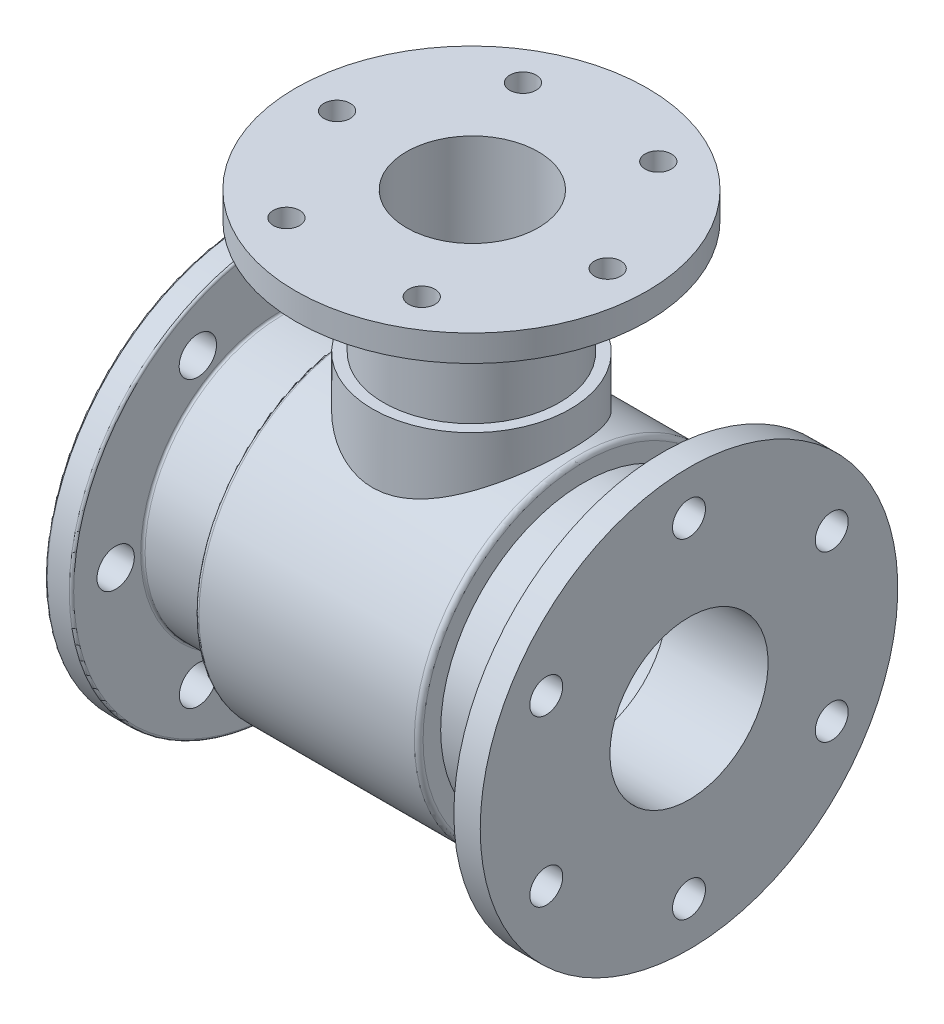
SolidWorks part; units mm, degrees
ref_plane "Front Plane" through (0, 0, 0) normal (0, 0, 1) x (1, 0, 0)
ref_plane "Top Plane" through (0, 0, 0) normal (0, 1, 0) x (1, 0, 0)
ref_plane "Right Plane" through (0, 0, 0) normal (1, 0, 0) x (0, 0, -1)
sketch "Sketch1" plane through (0, 0, 0) normal (0, 0, 1) x (1, 0, 0)
  line L0 (0, 0) -> (0, 122302.881) construction
  line L1 (0, 0) -> (122302.881, 0) construction
  line L2 (-87, -47.5) -> (-87, -52.5)
  line L3 (-87, -52.5) -> (-99, -52.5)
  line L4 (-99, -52.5) -> (-99, -95)
  line L5 (-99, -95) -> (-87, -95)
  line L6 (-87, -95) -> (-87, -62.5)
  line L7 (-87, -62.5) -> (-51, -62.5)
  line L8 (-51, -62.5) -> (-51, -73)
  line L9 (-49, -75) -> (49, -75)
  line L10 (51, -73) -> (51, -65)
  line L11 (51, -65) -> (73, -65)
  line L12 (73, -65) -> (73, -50)
  line L13 (73, -50) -> (87, -50)
  line L14 (87, -50) -> (87, -95)
  line L15 (87, -95) -> (99, -95)
  line L16 (99, -95) -> (99, -36)
  line L17 (99, -36) -> (53, -36)
  line L18 (53, -36) -> (53, -41.5)
  line L19 (51, -43.5) -> (36, -43.5)
  line L20 (36, -43.5) -> (36, -50.5)
  line L21 (34, -52.5) -> (-34, -52.5)
  line L22 (-36, -50.5) -> (-36, -47.5)
  line L23 (-36, -47.5) -> (-87, -47.5)
  line L24 (53, -41.5) -> (51, -43.5)
  arc A0 (-51, -73) -> (-49, -75) centre (-49, -73) ccw
  arc A1 (49, -75) -> (51, -73) centre (49, -73) ccw
  arc A2 (36, -50.5) -> (34, -52.5) centre (34, -50.5) cw
  arc A3 (-34, -52.5) -> (-36, -50.5) centre (-34, -50.5) cw
  point P23 (53, -43.5)
  point P28 (80, -50)
  point P29 (62, -65)
  dimension "D16" = 2
  dimension "D1" = 26
  dimension "D2" = 2
  dimension "D3" = 63
  dimension "D4" = 135
  dimension "D5" = 150
  dimension "D6" = 12
  dimension "D7" = 72
  dimension "D8" = 87
  dimension "D9" = 100
  dimension "D10" = 130
  dimension "D11" = 95
  dimension "D12" = 105
  dimension "D13" = 125
  dimension "D14" = 190
  dimension "D15" = 150
  dimension "D17" = 45
  dimension "D18" = 46
revolve "Revolve1" add sketch "Sketch1" angle 360 about L1
hole_wizard "Ø12.0mm Dowel Hole1" positions "Sketch2" profile "Sketch3" hole size "Ø12.0" standard "ANSI Metric"
sketch "Sketch2" plane through (99, 0, 0) normal (1, 0, 0) x (0, 0, -1)
  circle A0 centre (0, 0) radius 75 construction
  point P0 (0, 75)
  dimension "D1" = 150
sketch "Sketch3" plane through (99, 75, 0) normal (0, 1, 0) x (0, 0, -1)
  line L0 (0, 0) -> (0, 12)
  line L1 (0, 12) -> (7.5, 12)
  line L2 (7.5, 12) -> (7.5, 0)
  line L5 (7.5, 0) -> (0, 0)
  line L11 (0, -6.35) -> (0, 107.95) construction
  dimension "Thru Hole Dia." = 15
  dimension "Thru Hole Depth" = 12
pattern_circular "CirPattern1" count 6 over 360 about axis through (0, 0, 0) along (1, 0, 0) of "Ø12.0mm Dowel Hole1"
hole_wizard "Ø12.0mm Dowel Hole2" positions "3DSketch1" profile "Sketch4" hole size "Ø12.0" standard "ANSI Metric"
sketch3d "3DSketch1"
  line L0 (0, 0, 0) -> (0, 0, 50000) construction
  circle A2 centre (0, 0, 0) radius 75 construction
  point P0 (-99, -0.0509, 74.8976)
  point P16 (75, 0, 0)
  point P18 (-99, 2.118, 81.6126)
  point P19 (0, 0, 0)
  point P20 (-99, 0.1412, 74.8351)
  point P21 (-99, -0.0509, 74.8976)
  dimension "D1" = 150
sketch "Sketch4" plane through (-99, -0.0509, 74.8976) normal (0, 1, 0) x (0, 0, 1)
  line L0 (0, 0) -> (0, 12)
  line L1 (0, 12) -> (8.5, 12)
  line L2 (8.5, 12) -> (8.5, 0)
  line L5 (8.5, 0) -> (0, 0)
  line L11 (0, -6.35) -> (0, 107.95) construction
  dimension "Thru Hole Dia." = 17
  dimension "Thru Hole Depth" = 12
pattern_circular "CirPattern2" count 6 over 360 about axis through (0, 0, 0) along (1, 0, 0) of "Ø12.0mm Dowel Hole2"
sketch "Sketch5" plane through (0, 0, 0) normal (0, 0, 1) x (1, 0, 0)
  line L0 (0, 0) -> (0, 50000) construction
  line L1 (0, 155) -> (80, 155)
  line L2 (80, 155) -> (80, 143)
  line L3 (80, 143) -> (40, 143)
  line L4 (40, 143) -> (40, 91)
  line L5 (40, 91) -> (45, 91)
  line L6 (45, 91) -> (45, 75)
  line L7 (49, 75) -> (-49, 75) construction
  line L8 (0, 155) -> (0, 75)
  line L9 (0, 75) -> (45, 75)
  point P12 (40, 117)
  dimension "D1" = 80
  dimension "D2" = 80
  dimension "D3" = 90
  dimension "D4" = 155
  dimension "D5" = 12
  dimension "D6" = 64
revolve "Revolve2" add sketch "Sketch5" angle 360 about L0
sketch "Sketch6" plane through (0, 75, 0) normal (0, -1, 0) x (1, 0, 0)
  circle A1 centre (0, 0) radius 45
  circle A2 centre (0, 0) radius 45
  dimension "D1" = 0
extrude "Boss-Extrude1" add sketch "Sketch6" along normal up to surface up to face at (49, 0, 75)
hole_wizard "Ø12.0mm Dowel Hole3" positions "3DSketch2" profile "Sketch7" hole size "Ø12.0" standard "ANSI Metric"
sketch3d "3DSketch2"
  point P0 (0.2824, 155, -0.1412)
  point P3 (0, 0, 0)
  point P7 (0.2824, 155, -0.1412)
sketch "Sketch7" plane through (0.2824, 155, -0.1412) normal (1, 0, 0) x (0, 0, 1)
  line L0 (0, 0) -> (0, 102.5002)
  line L1 (0, 102.5002) -> (30, 102.5002)
  line L2 (30, 102.5002) -> (30, 0)
  line L5 (30, 0) -> (0, 0)
  line L11 (0, -6.35) -> (0, 107.95) construction
  dimension "Thru Hole Dia." = 60
  dimension "Thru Hole Depth" = 102.5002
hole_wizard "Ø12.0mm Dowel Hole4" positions "3DSketch3" profile "Sketch8" hole size "Ø12.0" standard "ANSI Metric"
sketch3d "3DSketch3"
  line L0 (0, 0, 0) -> (50000, 0, 0) construction
  circle A0 centre (0, 0, 0) radius 62.5 construction
  point P0 (62.1273, 155, 0.1412)
  point P9 (0, 62.5, 0)
  point P11 (62.1273, 155, 0.1412)
  dimension "D1" = 125
sketch "Sketch8" plane through (62.1273, 155, 0.1412) normal (1, 0, 0) x (0, 0, 1)
  line L0 (0, 0) -> (0, 12)
  line L1 (0, 12) -> (6, 12)
  line L2 (6, 12) -> (6, 0)
  line L5 (6, 0) -> (0, 0)
  line L11 (0, -6.35) -> (0, 107.95) construction
  dimension "Thru Hole Dia." = 12
  dimension "Thru Hole Depth" = 12
pattern_circular "CirPattern3" count 6 over 360 about axis through (0.2824, 0, -0.1412) along (0, 1, 0) of "Ø12.0mm Dowel Hole4"
fillet "Fillet1" radius 1 4 edges at (-51, 0, 62.5) (-87, 0, 62.5) (-87, 0, 95) (-99, 0, 95)
